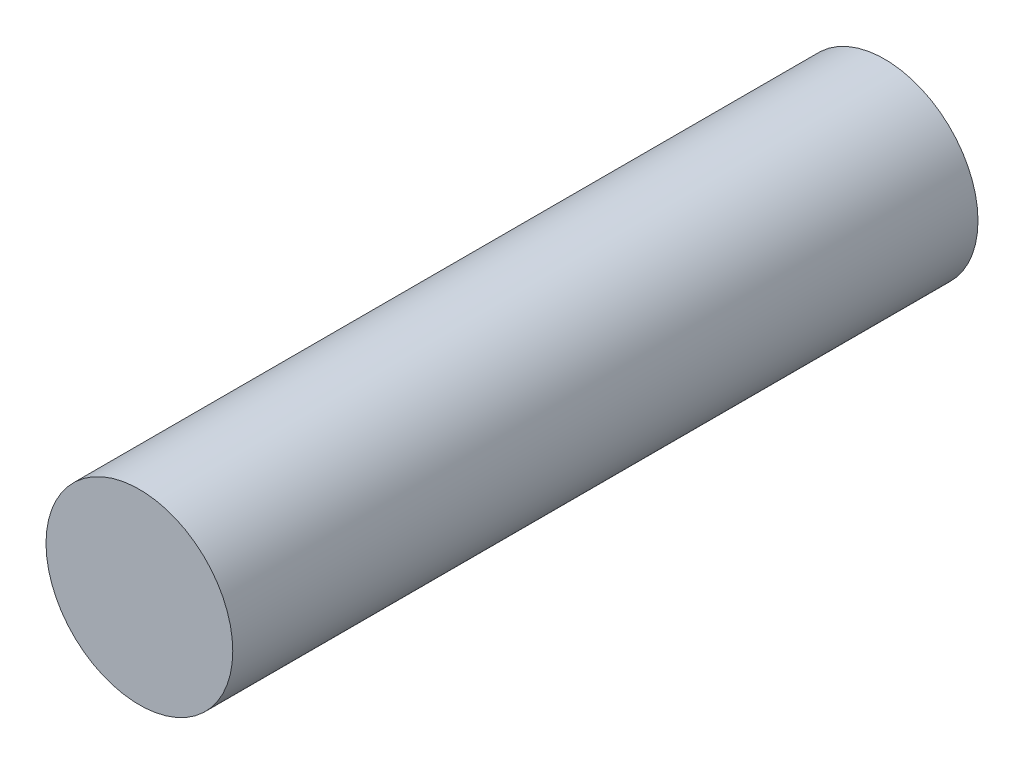
SolidWorks part; units mm, degrees
ref_plane "Front Plane" through (0, 0, 0) normal (0, 0, 1) x (1, 0, 0)
ref_plane "Top Plane" through (0, 0, 0) normal (0, 1, 0) x (1, 0, 0)
ref_plane "Right Plane" through (0, 0, 0) normal (1, 0, 0) x (0, 0, -1)
sketch "Sketch1" plane through (0, 0, 0) normal (0, 0, 1) x (1, 0, 0)
  circle A0 centre (0, 0) radius 6.35
  dimension "D1" = 12.7
extrude "Boss-Extrude1" add sketch "Sketch1" along normal blind 50.673
